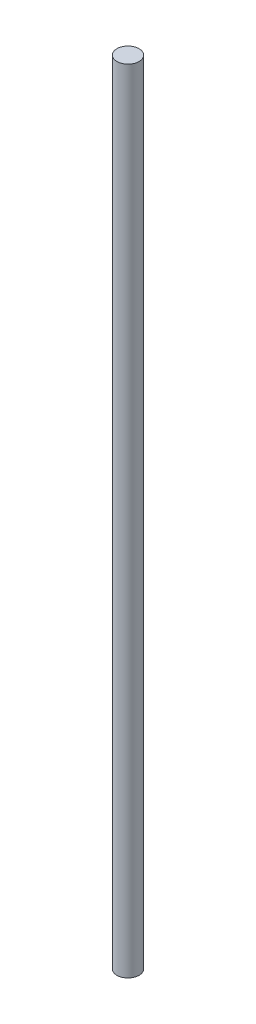
SolidWorks part; units mm, degrees
material "镀铬不锈钢"
ref_plane "前视基准面" through (0, 0, 0) normal (0, 0, 1) x (1, 0, 0)
ref_plane "上视基准面" through (0, 0, 0) normal (0, 1, 0) x (1, 0, 0)
ref_plane "右视基准面" through (0, 0, 0) normal (1, 0, 0) x (0, 0, -1)
sketch "草图1" plane through (0, 0, 0) normal (0, 1, 0) x (1, 0, 0)
  circle A0 centre (0, 0) radius 4
  dimension "D1" = 8
extrude "凸台-拉伸1" add sketch "草图1" along normal blind 285
